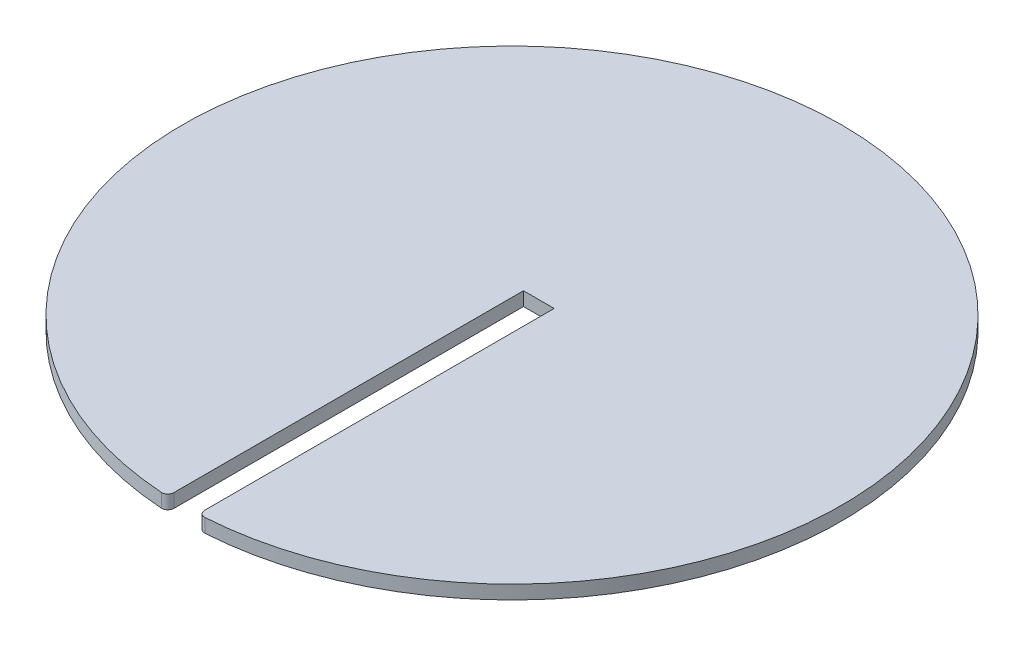
SolidWorks part; units mm, degrees
material "Custom Plastic"
ref_plane "Front Plane" through (0, 0, 0) normal (0, 0, 1) x (1, 0, 0)
ref_plane "Top Plane" through (0, 0, 0) normal (0, 1, 0) x (1, 0, 0)
ref_plane "Right Plane" through (0, 0, 0) normal (1, 0, 0) x (0, 0, -1)
sketch "Sketch1" plane through (0, 0, 0) normal (0, 1, 0) x (1, 0, 0)
  line L0 (2.4085, 1.9486) -> (2.4085, -33.01)
  line L1 (5.9585, 8.1486) -> (2.4085, 8.1486)
  line L2 (5.9585, 8.1486) -> (5.9585, 1.9486)
  line L3 (5.9585, 1.9486) -> (5.9585, -33.01)
  line L4 (2.4085, 8.1486) -> (2.4085, 1.9486)
  line L5 (5.9585, 8.1486) -> (2.4085, 1.9486) construction
  line L6 (5.9585, 1.9486) -> (2.4085, 8.1486) construction
  line L7 (-17.1481, 5.0486) -> (4.1835, 5.0486) construction
  arc A0 (5.9585, -33.01) -> (2.4085, -33.01) centre (4.1835, 5.0486) ccw
  point P0 (0, 0)
  dimension "D1" = 76.2
  dimension "D2" = 6.2
  dimension "D3" = 3.55
extrude "Boss-Extrude1" add sketch "Sketch1" along normal blind 1.5875
fillet "Fillet1" radius 0.7 2 edges at (5.9585, 0.7937, 33.01) (2.4085, 0.7937, 33.01)
